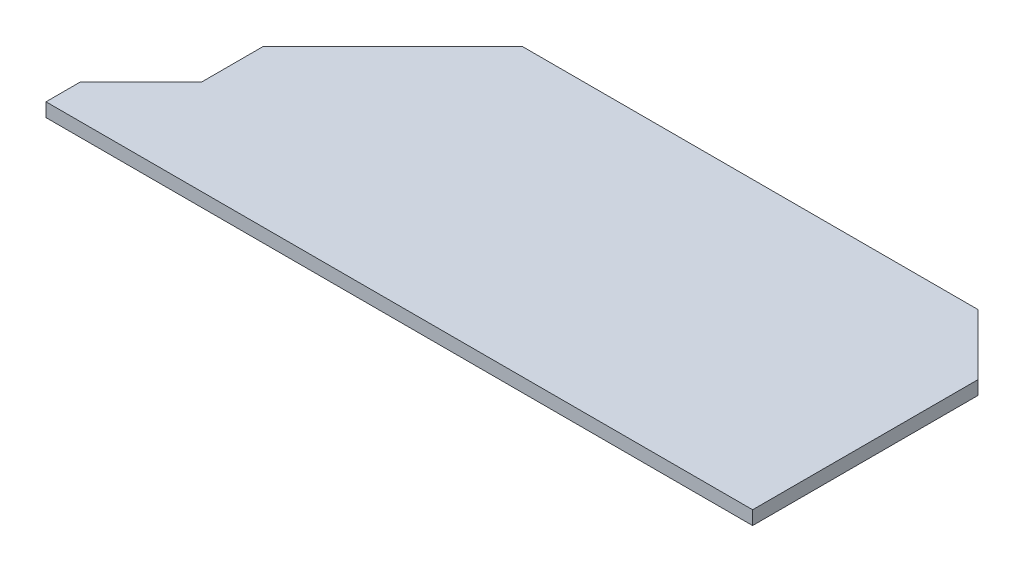
SolidWorks part; units mm, degrees
ref_plane "Front Plane" through (0, 0, 0) normal (0, 0, 1) x (1, 0, 0)
ref_plane "Top Plane" through (0, 0, 0) normal (0, 1, 0) x (1, 0, 0)
ref_plane "Right Plane" through (0, 0, 0) normal (1, 0, 0) x (0, 0, -1)
sketch "Sketch1" plane through (0, 0, 0) normal (0, 1, 0) x (1, 0, 0)
  line L0 (-39.1365, -29.6506) -> (84.3635, -29.6506)
  line L1 (84.3635, -29.6506) -> (84.3635, 9.7428)
  line L2 (84.3635, 9.7428) -> (73.7569, 20.3494)
  line L3 (73.7569, 20.3494) -> (-5.9024, 20.3494)
  line L4 (-5.9024, 20.3494) -> (-28.5299, -2.278)
  line L5 (-28.5299, -2.278) -> (-28.5299, -13.044)
  line L6 (-28.5299, -13.044) -> (-39.1365, -23.6506)
  line L7 (-39.1365, -23.6506) -> (-39.1365, -29.6506)
  dimension "D1" = 123.5
  dimension "D2" = 50
  dimension "D3" = 15
  dimension "D4" = 6
  dimension "D5" = 15
  dimension "D6" = 32
extrude "Boss-Extrude1" add sketch "Sketch1" along normal blind 2.4
sketch "Sketch2" plane through (0, 0, 0) normal (0, -1, 0) x (-1, 0, 0)
  line L1 (-5.9743, -17.8758) -> (-51.0295, -17.8758)
  line L2 (-5.9743, -17.8758) -> (-5.9743, -10.1924)
  line L3 (-5.9743, -10.1924) -> (-51.0295, -10.1924)
  line L4 (-51.0295, -17.8758) -> (-51.0295, -10.1924)
extrude "Boss-Extrude2" add sketch "Sketch2" along normal blind 2.8
